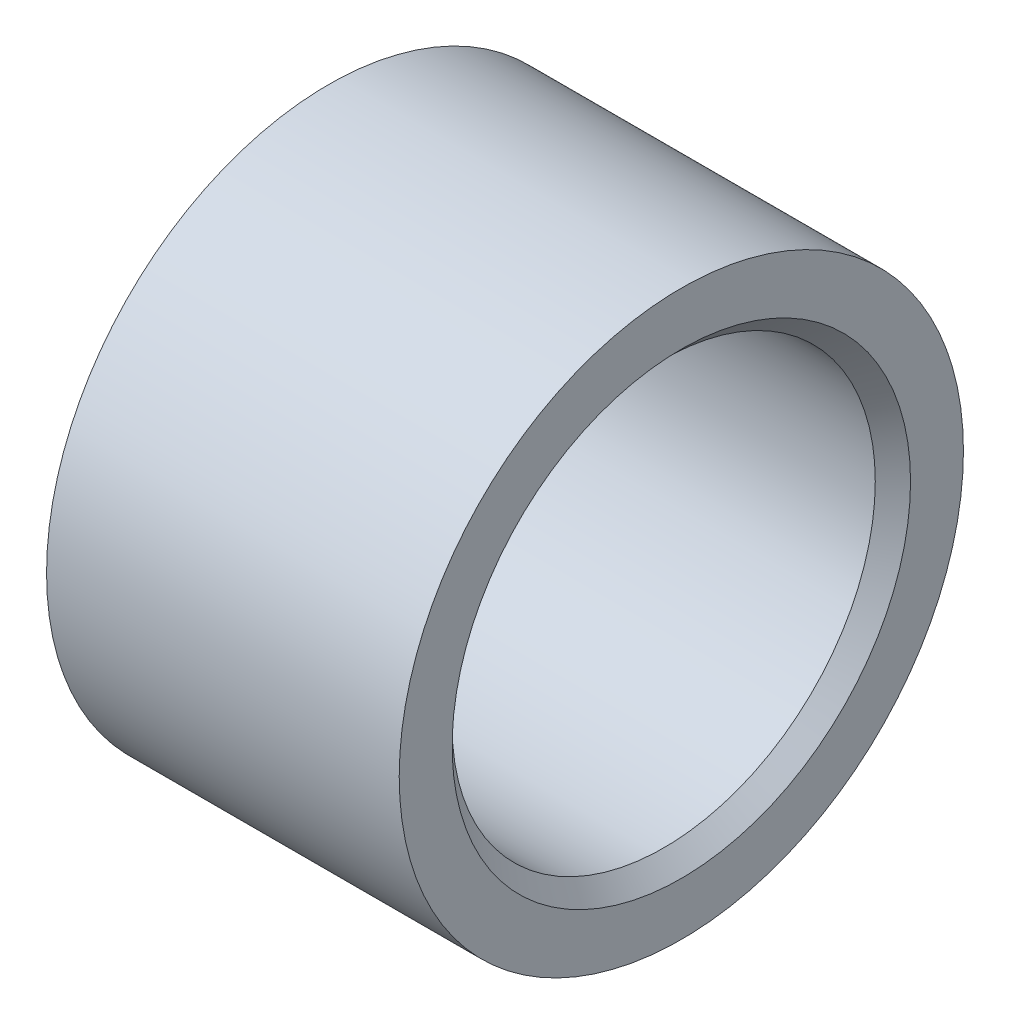
SolidWorks part; units mm, degrees
ref_plane "Płaszczyzna przednia" through (0, 0, 0) normal (0, 0, 1) x (1, 0, 0)
ref_plane "Płaszczyzna górna" through (0, 0, 0) normal (0, 1, 0) x (1, 0, 0)
ref_plane "Płaszczyzna prawa" through (0, 0, 0) normal (1, 0, 0) x (0, 0, -1)
sketch "Szkic1" plane through (0, 0, 0) normal (1, 0, 0) x (0, 0, -1)
  circle A0 centre (0, 0) radius 8
  circle A1 centre (0, 0) radius 6
  dimension "D1" = 12
  dimension "D2" = 16
extrude "Dodanie-wyciągnięcie1" add sketch "Szkic1" along normal blind 10
chamfer "Sfazowanie1" distance 0.5 angle 45 2 edges at (0, 0, -6) (10, 0, -6)
